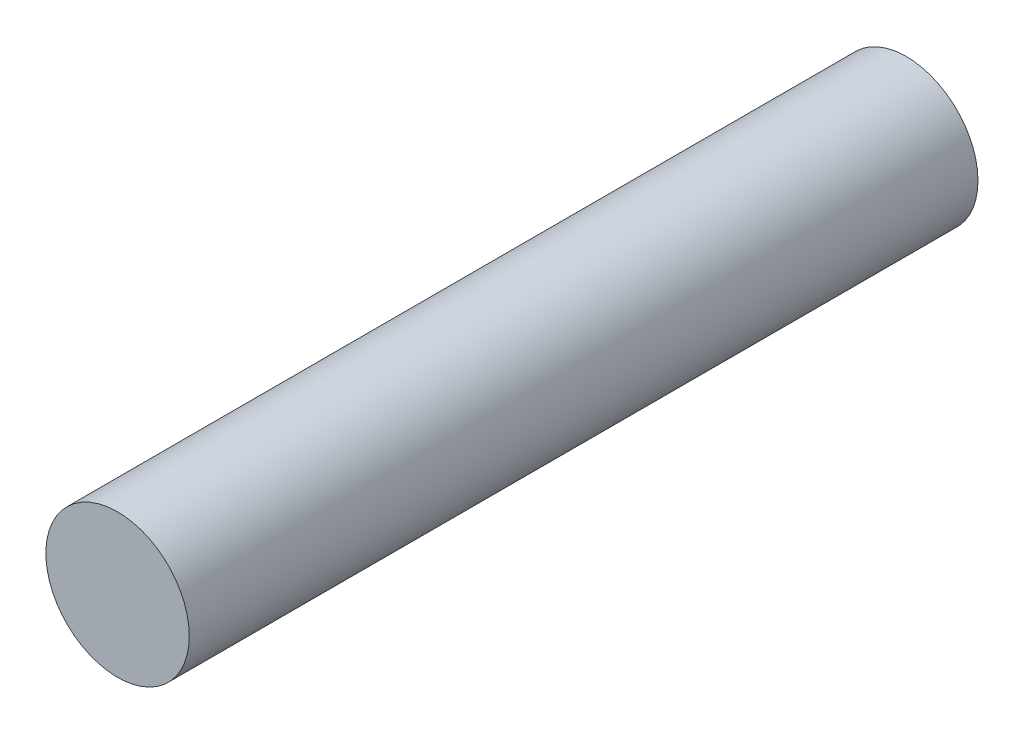
SolidWorks part; units mm, degrees
ref_plane "前视基准面" through (0, 0, 0) normal (0, 0, 1) x (1, 0, 0)
ref_plane "上视基准面" through (0, 0, 0) normal (0, 1, 0) x (1, 0, 0)
ref_plane "右视基准面" through (0, 0, 0) normal (1, 0, 0) x (0, 0, -1)
sketch "草图1" plane through (0, 0, 0) normal (0, 0, 1) x (1, 0, 0)
  circle A0 centre (-14.5759, 3.2588) radius 5
  dimension "D1" = 10
extrude "凸台-拉伸1" add sketch "草图1" along normal blind 55
